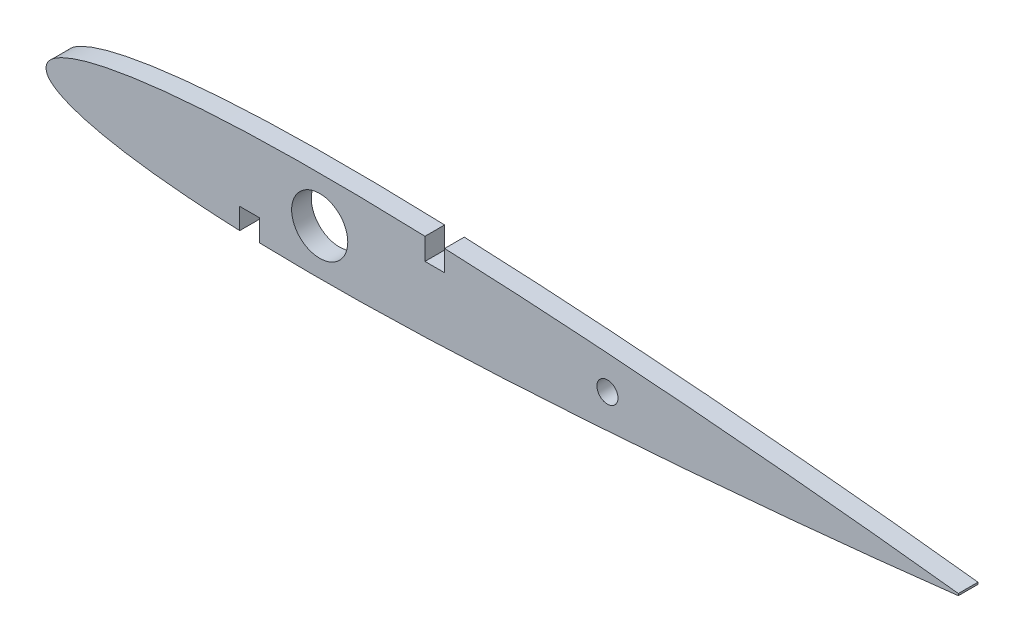
SolidWorks part; units mm, degrees
material "Фанера"
ref_plane "Спереди" through (0, 0, 0) normal (0, 0, 1) x (1, 0, 0)
ref_plane "Сверху" through (0, 0, 0) normal (0, 1, 0) x (1, 0, 0)
ref_plane "Справа" through (0, 0, 0) normal (1, 0, 0) x (0, 0, -1)
curve "Кривая1"
  spline degree 3 poles (200, 0.1365, 0) (199.688, 0.1729, 0) (198.8167, 0.2745, 0) (197.2359, 0.4561, 0) (195.145, 0.6923, 0) (192.7015, 0.9625, 0) (189.9816, 1.2561, 0) (187.0365, 1.566, 0) (183.905, 1.8867, 0) (180.6179, 2.2137, 0) (177.2012, 2.5436, 0) (173.6771, 2.8733, 0) (170.065, 3.2002, 0) (166.3822, 3.5221, 0) (162.6444, 3.8368, 0) (158.8659, 4.1424, 0) (155.06, 4.437, 0) (151.2387, 4.7189, 0) (147.4135, 4.9862, 0) (143.595, 5.2374, 0) (139.7935, 5.4706, 0) (136.0183, 5.6841, 0) (132.2786, 5.8765, 0) (128.5831, 6.0459, 0) (124.94, 6.191, 0) (121.3572, 6.3103, 0) (117.8424, 6.4025, 0) (114.4029, 6.4663, 0) (111.0457, 6.5008, 0) (107.7777, 6.505, 0) (104.6056, 6.4782, 0) (101.5356, 6.4201, 0) (98.5742, 6.3302, 0) (95.7272, 6.2086, 0) (93.0006, 6.0555, 0) (90.4002, 5.8711, 0) (87.9314, 5.6561, 0) (85.5998, 5.4114, 0) (83.4106, 5.1378, 0) (81.3691, 4.8365, 0) (79.4802, 4.5088, 0) (77.7488, 4.156, 0) (76.1798, 3.7796, 0) (74.7776, 3.3811, 0) (73.5467, 2.9618, 0) (72.4905, 2.523, 0) (71.6134, 2.0657, 0) (70.9148, 1.5895, 0) (70.4055, 1.0913, 0) (70.0654, 0.5615, 0) (70.0211, 0.181, 0) (70, 0, 0) knots 0 0 0 0 0.007145 0.019956 0.036196 0.055011 0.075879 0.098429 0.122376 0.147488 0.173572 0.20046 0.228005 0.256076 0.284555 0.313333 0.34231 0.371393 0.400496 0.429538 0.458442 0.487136 0.515552 0.543624 0.57129 0.598491 0.62517 0.651272 0.676746 0.701542 0.725611 0.748908 0.771388 0.793008 0.813728 0.833508 0.85231 0.870097 0.886836 0.902493 0.917037 0.930441 0.94268 0.953734 0.96359 0.972247 0.979722 0.986065 0.991385 0.995901 1 1 1 1
curve "Кривая2"
  spline degree 3 poles (70, 0, 0) (70.0211, -0.181, 0) (70.0654, -0.5615, 0) (70.4055, -1.0913, 0) (70.9148, -1.5895, 0) (71.6134, -2.0657, 0) (72.4905, -2.523, 0) (73.5467, -2.9618, 0) (74.7776, -3.3811, 0) (76.1798, -3.7796, 0) (77.7488, -4.156, 0) (79.4802, -4.5088, 0) (81.3691, -4.8365, 0) (83.4106, -5.1378, 0) (85.5998, -5.4114, 0) (87.9314, -5.6561, 0) (90.4002, -5.8711, 0) (93.0006, -6.0555, 0) (95.7272, -6.2086, 0) (98.5742, -6.3302, 0) (101.5356, -6.4201, 0) (104.6056, -6.4782, 0) (107.7777, -6.505, 0) (111.0457, -6.5008, 0) (114.4029, -6.4663, 0) (117.8424, -6.4025, 0) (121.3572, -6.3103, 0) (124.94, -6.191, 0) (128.5831, -6.0459, 0) (132.2786, -5.8765, 0) (136.0183, -5.6841, 0) (139.7935, -5.4706, 0) (143.595, -5.2374, 0) (147.4135, -4.9862, 0) (151.2387, -4.7189, 0) (155.06, -4.437, 0) (158.8659, -4.1424, 0) (162.6444, -3.8368, 0) (166.3822, -3.5221, 0) (170.065, -3.2002, 0) (173.6771, -2.8733, 0) (177.2012, -2.5436, 0) (180.6179, -2.2137, 0) (183.905, -1.8867, 0) (187.0365, -1.566, 0) (189.9816, -1.2561, 0) (192.7015, -0.9625, 0) (195.145, -0.6923, 0) (197.2359, -0.4561, 0) (198.8167, -0.2745, 0) (199.688, -0.1729, 0) (200, -0.1365, 0) knots 0 0 0 0 0.004099 0.008615 0.013935 0.020278 0.027753 0.03641 0.046266 0.05732 0.069559 0.082963 0.097507 0.113164 0.129903 0.14769 0.166492 0.186272 0.206992 0.228612 0.251092 0.274389 0.298458 0.323254 0.348728 0.37483 0.401509 0.42871 0.456376 0.484448 0.512864 0.541558 0.570462 0.599504 0.628607 0.65769 0.686667 0.715445 0.743924 0.771995 0.79954 0.826428 0.852512 0.877624 0.901571 0.924121 0.944989 0.963804 0.980044 0.992855 1 1 1 1
sketch "Эскиз1" plane through (0, 0, 0) normal (0, 0, 1) x (1, 0, 0)
  line L0 (200, 0.1365) -> (200, -0.1365)
  line L1 (100.4, -6.3839) -> (100.4, -3.2866)
  line L2 (100.4, -3.2866) -> (97.6, -3.2866)
  line L3 (97.6, -3.2866) -> (97.6, -6.2866)
  line L4 (124, 6.2207) -> (124, 3.116)
  line L5 (124, 3.116) -> (126.8, 3.116)
  line L6 (126.8, 3.116) -> (126.8, 6.116)
  circle A0 centre (109, 0) radius 4
  arc A1 (150, 4.8046) -> (150, -4.8046) centre (150, 0) ccw
  arc A2 (142.9507, 5.2753) -> (142.9507, -5.2753) centre (150, 0) ccw
  circle A4 centre (150, 0) radius 1.5
  spline S0 degree 3 poles (-6604.9726, -2096.9549) (186.3332, 58.0177) (64.4426, 8.1991) (70.4055, -1.0913) (70.9148, -1.5895) (71.6134, -2.0657) (72.4905, -2.523) (73.5467, -2.9618) (74.7776, -3.3811) (76.1798, -3.7796) (77.7488, -4.156) (79.4802, -4.5088) (81.3691, -4.8365) (83.4106, -5.1378) (85.5998, -5.4114) (87.9314, -5.6561) (90.4002, -5.8711) (93.0006, -6.0555) (95.7272, -6.2086) (98.5742, -6.3302) (101.5356, -6.4201) (104.6056, -6.4782) (107.7777, -6.505) (111.0457, -6.5008) (114.4029, -6.4663) (117.8424, -6.4025) (121.3572, -6.3103) (124.94, -6.191) (128.5831, -6.0459) (132.2786, -5.8765) (136.0183, -5.6841) (139.7935, -5.4706) (143.595, -5.2374) (147.4135, -4.9862) (151.2387, -4.7189) (155.06, -4.437) (158.8659, -4.1424) (162.6444, -3.8368) (166.3822, -3.5221) (170.065, -3.2002) (174.8191, -2.7699) (179.4417, -2.3307) (183.905, -1.8867) (187.0365, -1.566) (189.9816, -1.2561) (192.7015, -0.9625) (195.145, -0.6923) (197.2359, -0.4561) (302.0269, 11.5824) (403.6317, 44.8697) (1315.1992, -6901.8264) knots -0.230414 -0.230414 -0.230414 -0.230414 0.004099 0.008615 0.013935 0.020278 0.027753 0.03641 0.046266 0.05732 0.069559 0.082963 0.097507 0.113164 0.129903 0.14769 0.166492 0.186272 0.206992 0.228612 0.251092 0.274389 0.298458 0.323254 0.348728 0.37483 0.401509 0.42871 0.456376 0.484448 0.512864 0.541558 0.570462 0.599504 0.628607 0.65769 0.686667 0.715445 0.743924 0.771995 0.79954 0.852512 0.877624 0.901571 0.924121 0.944989 0.963804 0.980044 0.992855 3.363271 3.363271 3.363271 3.363271 only from (70, 0) to (200, -0.1365) construction
  spline S1 degree 3 poles (1315.2065, 6901.882) (403.6322, -44.8698) (302.0272, -11.5824) (197.2359, 0.4561) (195.145, 0.6923) (192.7015, 0.9625) (189.9816, 1.2561) (187.0365, 1.566) (183.905, 1.8867) (179.4417, 2.3307) (174.8191, 2.7699) (170.065, 3.2002) (166.3822, 3.5221) (162.6444, 3.8368) (158.8659, 4.1424) (155.06, 4.437) (151.2387, 4.7189) (147.4135, 4.9862) (143.595, 5.2374) (139.7935, 5.4706) (136.0183, 5.6841) (132.2786, 5.8765) (128.5831, 6.0459) (124.94, 6.191) (121.3572, 6.3103) (117.8424, 6.4025) (114.4029, 6.4663) (111.0457, 6.5008) (107.7777, 6.505) (104.6056, 6.4782) (101.5356, 6.4201) (98.5742, 6.3302) (95.7272, 6.2086) (93.0006, 6.0555) (90.4002, 5.8711) (87.9314, 5.6561) (85.5998, 5.4114) (83.4106, 5.1378) (81.3691, 4.8365) (79.4802, 4.5088) (77.7488, 4.156) (76.1798, 3.7796) (74.7776, 3.3811) (73.5467, 2.9618) (72.4905, 2.523) (71.6134, 2.0657) (70.9148, 1.5895) (70.4055, 1.0913) (64.4431, -8.1984) (186.3138, -58.0097) (-6603.3138, 2096.4286) knots -2.363277 -2.363277 -2.363277 -2.363277 0.007145 0.019956 0.036196 0.055011 0.075879 0.098429 0.122376 0.147488 0.20046 0.228005 0.256076 0.284555 0.313333 0.34231 0.371393 0.400496 0.429538 0.458442 0.487136 0.515552 0.543624 0.57129 0.598491 0.62517 0.651272 0.676746 0.701542 0.725611 0.748908 0.771388 0.793008 0.813728 0.833508 0.85231 0.870097 0.886836 0.902493 0.917037 0.930441 0.94268 0.953734 0.96359 0.972247 0.979722 0.986065 0.991385 0.995901 1.230395 1.230395 1.230395 1.230395 only from (200, 0.1365) to (70, 0) construction
  spline S2 degree 3 poles (70, 0) (70.0211, -0.181) (70.0654, -0.5615) (70.4055, -1.0913) (70.9148, -1.5895) (71.6134, -2.0657) (72.4905, -2.523) (73.5467, -2.9618) (74.7776, -3.3811) (76.1798, -3.7796) (77.7488, -4.156) (79.4802, -4.5088) (81.3691, -4.8365) (83.4106, -5.1378) (85.5998, -5.4114) (87.9314, -5.6561) (90.4002, -5.8711) (93.0006, -6.0555) (95.4152, -6.1911) (96.9625, -6.2607) (97.6, -6.2866) knots 0 0 0 0 0.004099 0.008615 0.013935 0.020278 0.027753 0.03641 0.046266 0.05732 0.069559 0.082963 0.097507 0.113164 0.129903 0.14769 0.166492 0.186272 0.206992 0.221505 0.221505 0.221505 0.221505
  spline S3 degree 3 poles (200, 0.1365) (199.688, 0.1729) (198.8167, 0.2745) (197.2359, 0.4561) (195.145, 0.6923) (192.7015, 0.9625) (189.9816, 1.2561) (187.0365, 1.566) (183.905, 1.8867) (179.4417, 2.3307) (174.8191, 2.7699) (170.065, 3.2002) (166.3822, 3.5221) (162.6444, 3.8368) (158.8659, 4.1424) (155.06, 4.437) (151.2387, 4.7189) (147.4135, 4.9862) (143.595, 5.2374) (139.7935, 5.4706) (136.0183, 5.6841) (132.2786, 5.8765) (129.2098, 6.0172) (127.3884, 6.0925) (126.8, 6.116) knots 0 0 0 0 0.007145 0.019956 0.036196 0.055011 0.075879 0.098429 0.122376 0.147488 0.20046 0.228005 0.256076 0.284555 0.313333 0.34231 0.371393 0.400496 0.429538 0.458442 0.487136 0.515552 0.543624 0.55702 0.55702 0.55702 0.55702
  spline S4 degree 3 poles (100.4, -6.3839) (100.7666, -6.3946) (102.157, -6.4319) (104.6056, -6.4782) (107.7777, -6.505) (111.0457, -6.5008) (114.4029, -6.4663) (117.8424, -6.4025) (121.3572, -6.3103) (124.94, -6.191) (128.5831, -6.0459) (132.2786, -5.8765) (136.0183, -5.6841) (139.7935, -5.4706) (143.595, -5.2374) (147.4135, -4.9862) (151.2387, -4.7189) (155.06, -4.437) (158.8659, -4.1424) (162.6444, -3.8368) (166.3822, -3.5221) (170.065, -3.2002) (174.8191, -2.7699) (179.4417, -2.3307) (183.905, -1.8867) (187.0365, -1.566) (189.9816, -1.2561) (192.7015, -0.9625) (195.145, -0.6923) (197.2359, -0.4561) (198.8167, -0.2745) (199.688, -0.1729) (200, -0.1365) knots 0.242749 0.242749 0.242749 0.242749 0.251092 0.274389 0.298458 0.323254 0.348728 0.37483 0.401509 0.42871 0.456376 0.484448 0.512864 0.541558 0.570462 0.599504 0.628607 0.65769 0.686667 0.715445 0.743924 0.771995 0.79954 0.852512 0.877624 0.901571 0.924121 0.944989 0.963804 0.980044 0.992855 1 1 1 1
  spline S5 degree 3 poles (124, 6.2207) (123.1115, 6.2516) (121.0507, 6.3184) (117.8424, 6.4025) (114.4029, 6.4663) (111.0457, 6.5008) (107.7777, 6.505) (104.6056, 6.4782) (101.5356, 6.4201) (98.5742, 6.3302) (95.7272, 6.2086) (93.0006, 6.0555) (90.4002, 5.8711) (87.9314, 5.6561) (85.5998, 5.4114) (83.4106, 5.1378) (81.3691, 4.8365) (79.4802, 4.5088) (77.7488, 4.156) (76.1798, 3.7796) (74.7776, 3.3811) (73.5467, 2.9618) (72.4905, 2.523) (71.6134, 2.0657) (70.9148, 1.5895) (70.4055, 1.0913) (70.0654, 0.5615) (70.0211, 0.181) (70, 0) knots 0.578266 0.578266 0.578266 0.578266 0.598491 0.62517 0.651272 0.676746 0.701542 0.725611 0.748908 0.771388 0.793008 0.813728 0.833508 0.85231 0.870097 0.886836 0.902493 0.917037 0.930441 0.94268 0.953734 0.96359 0.972247 0.979722 0.986065 0.991385 0.995901 1 1 1 1
  point P13 (99, -3.2866)
  dimension "D1" = 8
  dimension "D11" = 4.8046
  dimension "D12" = 8.8046
  dimension "D13" = 3
  dimension "D2" = 39
  dimension "D8" = 2.8
  dimension "D9" = 10
  dimension "D3" = 3
  dimension "D4" = 2.8
  dimension "D5" = 15
  dimension "D6" = 3
  dimension "D10" = 80
  dimension "D7" = 9.6092
extrude "Бобышка-Вытянуть1" add sketch "Эскиз1" along normal mid plane 2.8 contours L4 S5 S2 L3 L2 L1 S4 A2 S3 L6 L5 A0 | A2 S4 A1 S3 | A1 S4 L0 S3 A4
equation "\"D11@Эскиз1\"=\"D7@Эскиз1\"/2"
equation "\"D12@Эскиз1\"=\"D11@Эскиз1\"+4"
